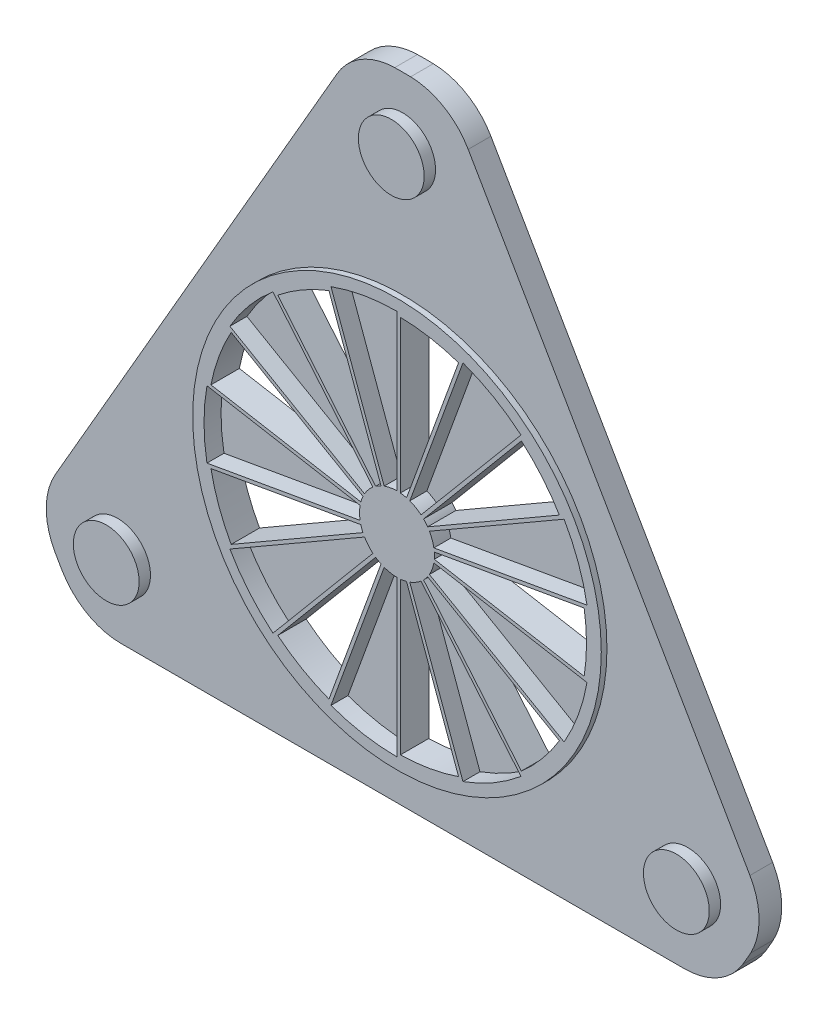
SolidWorks part; units mm, degrees
ref_plane "Спереди" through (0, 0, 0) normal (0, 0, 1) x (1, 0, 0)
ref_plane "Сверху" through (0, 0, 0) normal (0, 1, 0) x (1, 0, 0)
ref_plane "Справа" through (0, 0, 0) normal (1, 0, 0) x (0, 0, -1)
sketch "Sketch1" plane through (0, 0, 0) normal (0, 0, 1) x (1, 0, 0)
  line L0 (3.9, 6.755) -> (7.8, 0) construction
  line L2 (5.85, 10.1325) -> (11.7, 0) construction
  line L4 (7.8, 13.51) -> (15.6, 0) construction
  circle A61 centre (0, 0) radius 20
  circle A131 centre (0, 0) radius 1.25
  circle A484 centre (3.9, 0) radius 1.25
  circle A485 centre (7.8, 0) radius 1.25
  circle A486 centre (11.7, 0) radius 1.25
  circle A487 centre (15.6, 0) radius 1.25
  circle A488 centre (1.95, -3.3775) radius 1.25
  circle A489 centre (3.9, -6.755) radius 1.25
  circle A490 centre (5.85, -10.1325) radius 1.25
  circle A491 centre (7.8, -13.51) radius 1.25
  circle A492 centre (-1.95, -3.3775) radius 1.25
  circle A493 centre (-3.9, -6.755) radius 1.25
  circle A494 centre (-5.85, -10.1325) radius 1.25
  circle A495 centre (-7.8, -13.51) radius 1.25
  circle A496 centre (-3.9, 0) radius 1.25
  circle A497 centre (-7.8, 0) radius 1.25
  circle A498 centre (-11.7, 0) radius 1.25
  circle A499 centre (-15.6, 0) radius 1.25
  circle A500 centre (-1.95, 3.3775) radius 1.25
  circle A501 centre (-3.9, 6.755) radius 1.25
  circle A502 centre (-5.85, 10.1325) radius 1.25
  circle A503 centre (-7.8, 13.51) radius 1.25
  circle A504 centre (1.95, 3.3775) radius 1.25
  circle A505 centre (3.9, 6.755) radius 1.25
  circle A506 centre (5.85, 10.1325) radius 1.25
  circle A507 centre (7.8, 13.51) radius 1.25
  circle A508 centre (5.85, 3.3775) radius 1.25
  circle A509 centre (7.8, 6.755) radius 1.25
  circle A510 centre (9.75, 3.3775) radius 1.25
  circle A511 centre (11.7, 6.755) radius 1.25
  circle A512 centre (9.7491, 10.1341) radius 1.25
  circle A513 centre (13.6509, 3.3759) radius 1.25
  circle A514 centre (5.85, -3.3791) radius 1.25
  circle A515 centre (9.75, -3.3791) radius 1.25
  circle A516 centre (7.8, -6.7566) radius 1.25
  circle A517 centre (11.7, -6.7566) radius 1.25
  circle A518 centre (9.7491, -10.1356) radius 1.25
  circle A519 centre (13.6509, -3.3775) radius 1.25
  circle A520 centre (-0.0013, -6.7573) radius 1.25
  circle A521 centre (1.9487, -10.1348) radius 1.25
  circle A522 centre (-1.9513, -10.1348) radius 1.25
  circle A523 centre (-0.0013, -13.5123) radius 1.25
  circle A524 centre (-3.9032, -13.5123) radius 1.25
  circle A525 centre (3.9005, -13.5123) radius 1.25
  circle A526 centre (-5.8527, -3.3791) radius 1.25
  circle A527 centre (-7.8027, -6.7566) radius 1.25
  circle A528 centre (-9.7527, -3.3791) radius 1.25
  circle A529 centre (-11.7027, -6.7566) radius 1.25
  circle A530 centre (-13.6536, -3.3775) radius 1.25
  circle A531 centre (-9.7518, -10.1356) radius 1.25
  circle A532 centre (-5.8527, 3.3775) radius 1.25
  circle A533 centre (-9.7527, 3.3775) radius 1.25
  circle A534 centre (-7.8027, 6.755) radius 1.25
  circle A535 centre (-11.7027, 6.755) radius 1.25
  circle A536 centre (-9.7518, 10.1341) radius 1.25
  circle A537 centre (-13.6536, 3.3759) radius 1.25
  circle A538 centre (-0.0014, 6.7558) radius 1.25
  circle A539 centre (-1.9514, 10.1333) radius 1.25
  circle A540 centre (1.9486, 10.1333) radius 1.25
  circle A541 centre (-0.0014, 13.5108) radius 1.25
  circle A542 centre (3.9005, 13.5108) radius 1.25
  circle A543 centre (-3.9032, 13.5108) radius 1.25
  circle A544 centre (13.65, -1.1258) radius 2.2517 construction
  circle A545 centre (11.7009, -4.5044) radius 2.2522 construction
  circle A546 centre (9.75, -7.8834) radius 2.2522 construction
  circle A547 centre (7.7987, -11.2591) radius 2.2509 construction
  circle A548 centre (13.65, -1.1258) radius 0.65
  circle A549 centre (11.7009, -4.5044) radius 0.65
  circle A550 centre (9.75, -7.8834) radius 0.65
  circle A551 centre (7.7987, -11.2591) radius 0.65
  circle A552 centre (9.75, -1.1258) radius 0.65
  circle A553 centre (7.8009, -4.5044) radius 0.65
  circle A554 centre (5.85, -7.8834) radius 0.65
  circle A555 centre (3.8987, -11.2591) radius 0.65
  circle A556 centre (5.85, -1.1258) radius 0.65
  circle A557 centre (3.9009, -4.5044) radius 0.65
  circle A558 centre (1.95, -7.8834) radius 0.65
  circle A559 centre (-0.0013, -11.2591) radius 0.65
  circle A560 centre (1.95, -1.1258) radius 0.65
  circle A561 centre (0.0009, -4.5044) radius 0.65
  circle A562 centre (-1.95, -7.8834) radius 0.65
  circle A563 centre (-3.9013, -11.2591) radius 0.65
  circle A564 centre (-1.95, -1.1258) radius 0.65
  circle A565 centre (-3.8991, -4.5044) radius 0.65
  circle A566 centre (-5.85, -7.8834) radius 0.65
  circle A567 centre (-7.8013, -11.2591) radius 0.65
  circle A568 centre (-5.85, -1.1258) radius 0.65
  circle A569 centre (-7.7991, -4.5044) radius 0.65
  circle A570 centre (-9.75, -7.8834) radius 0.65
  circle A572 centre (-9.75, -1.1258) radius 0.65
  circle A573 centre (-11.6991, -4.5044) radius 0.65
  circle A576 centre (-13.65, -1.1258) radius 0.65
  circle A587 centre (0, 2.2517) radius 2.2517 construction
  circle A588 centre (0, 2.2517) radius 0.65
  circle A589 centre (3.9, 2.2517) radius 0.65
  circle A590 centre (7.8, 2.2517) radius 0.65
  circle A591 centre (11.7, 2.2517) radius 0.65
  circle A592 centre (15.6, 2.2517) radius 0.65
  circle A593 centre (1.9491, 5.6297) radius 2.2522 construction
  circle A594 centre (1.9491, 5.6297) radius 0.65
  circle A595 centre (5.8491, 5.6297) radius 0.65
  circle A596 centre (9.7491, 5.6297) radius 0.65
  circle A597 centre (13.6491, 5.6297) radius 0.65
  circle A598 centre (3.8991, 9.0072) radius 2.2522 construction
  circle A599 centre (3.8991, 9.0072) radius 0.65
  circle A600 centre (7.7991, 9.0072) radius 0.65
  circle A601 centre (11.6991, 9.0072) radius 0.65
  circle A602 centre (5.85, 12.3842) radius 2.2517 construction
  circle A603 centre (5.85, 12.3842) radius 0.65
  circle A604 centre (9.75, 12.3842) radius 0.65
  circle A605 centre (5.85, -14.6358) radius 0.65
  circle A606 centre (1.9509, -14.6353) radius 0.65
  circle A607 centre (-1.9491, -14.6353) radius 0.65
  circle A608 centre (-5.85, -14.6358) radius 0.65
  circle A609 centre (-15.6, 2.2517) radius 0.65
  circle A610 centre (-13.65, 5.6281) radius 0.65
  circle A611 centre (-11.7, 9.0056) radius 0.65
  circle A612 centre (-9.75, 12.3842) radius 0.65
  circle A613 centre (-5.85, 12.3842) radius 0.65
  circle A614 centre (-1.95, 12.3842) radius 0.65
  circle A615 centre (1.95, 12.3842) radius 0.65
  circle A616 centre (-7.8, 9.0056) radius 0.65
  circle A617 centre (-9.75, 5.6281) radius 0.65
  circle A618 centre (-11.7, 2.2517) radius 0.65
  circle A619 centre (-3.9, 9.0056) radius 0.65
  circle A620 centre (-5.85, 5.6281) radius 0.65
  circle A621 centre (-7.8, 2.2517) radius 0.65
  circle A622 centre (0, 9.0056) radius 0.65
  circle A623 centre (-1.95, 5.6281) radius 0.65
  circle A624 centre (-3.9, 2.2517) radius 0.65
  circle A625 centre (-15.5991, -4.5044) radius 0.65
  circle A626 centre (-13.65, -7.8834) radius 0.65
  circle A627 centre (-17.55, -7.8834) radius 0.65
  circle A628 centre (-19.5013, -11.2591) radius 0.65
  circle A629 centre (-15.6013, -11.2591) radius 0.65
  circle A630 centre (-11.7013, -11.2591) radius 0.65
  point P51 (0, 0)
  point P125 (-0.0013, -0.0008)
  point P231 (0, 0)
  dimension "D1" = 5
  dimension "D3" = 6
  dimension "D5" = 8
  dimension "D7" = 4
  dimension "D11" = 4
  dimension "D2" = 6
  dimension "D6" = 5
  dimension "D8" = 3
  dimension "D9" = 2
  dimension "D4" = 1.3
  dimension "D10" = 3
ref_plane "Plane1" through (0, 0, 10) normal (0, 0, 1) x (1, 0, 0)
sketch "Sketch2" plane through (0, 0, 10) normal (0, 0, 1) x (1, 0, 0)
  line L0 (0, 2.9883) -> (0, 17)
  line L62 (1.0221, 2.8081) -> (5.8143, 15.9748)
  line L71 (1.9208, 2.2892) -> (10.9274, 13.0228)
  line L92 (2.588, 1.4942) -> (14.7224, 8.5)
  line L101 (2.9429, 0.5189) -> (16.7417, 2.952)
  line L110 (2.9429, -0.5189) -> (16.7417, -2.952)
  line L119 (2.588, -1.4942) -> (14.7224, -8.5)
  line L124 (1.9208, -2.2892) -> (10.9274, -13.0228)
  line L133 (1.0221, -2.8081) -> (5.8143, -15.9748)
  line L142 (0, -2.9883) -> (0, -17)
  line L151 (-1.0221, -2.8081) -> (-5.8143, -15.9748)
  line L160 (-1.9208, -2.2892) -> (-10.9274, -13.0228)
  line L165 (-2.588, -1.4942) -> (-14.7224, -8.5)
  line L168 (-2.9429, -0.5189) -> (-16.7417, -2.952)
  line L171 (-2.9429, 0.5189) -> (-16.7417, 2.952)
  line L174 (-2.588, 1.4942) -> (-14.7224, 8.5)
  line L177 (-1.9208, 2.2892) -> (-10.9274, 13.0228)
  line L180 (-1.0221, 2.8081) -> (-5.8143, 15.9748)
  line L183 (0.3, 3.2863) -> (0.3, 16.6948)
  line L185 (5.4281, 15.7906) -> (0.8421, 3.1908)
  line L186 (14.3082, 8.6072) -> (2.696, 1.903)
  line L187 (2.3422, 2.3246) -> (10.9611, 12.5962)
  line L188 (16.4933, -2.6036) -> (3.2885, -0.2752)
  line L189 (3.2885, 0.2752) -> (16.4933, 2.6036)
  line L190 (10.9611, -12.5962) -> (2.3422, -2.3246)
  line L191 (2.696, -1.903) -> (14.3082, -8.6072)
  line L192 (0.3, -16.6948) -> (0.3, -3.2863)
  line L193 (0.8421, -3.1908) -> (5.4281, -15.7906)
  line L194 (-10.5014, -12.9818) -> (-1.8826, -2.7103)
  line L195 (-1.4059, -2.9855) -> (-5.9919, -15.5854)
  line L196 (-16.3891, -3.1945) -> (-3.1843, -0.8661)
  line L197 (-2.996, -1.3834) -> (-14.6082, -8.0876)
  line L198 (-14.6082, 8.0876) -> (-2.996, 1.3834)
  line L199 (-3.1843, 0.8661) -> (-16.3891, 3.1945)
  line L200 (-5.9919, 15.5854) -> (-1.4059, 2.9855)
  line L201 (-1.8826, 2.7103) -> (-10.5014, 12.9818)
  circle A52 centre (0, 0) radius 17
  circle A53 centre (0, 0) radius 18
  circle A199 centre (0, 0) radius 2.9883
  circle A245 centre (0, 0) radius 18.85
  circle A246 centre (0, 0) radius 3.3
  circle A247 centre (0, 0) radius 16.6975
  point P39 (0, 0)
  point P80 (0, 0)
  point P108 (0, 0)
  dimension "D1" = 18
  dimension "D4" = 9
  dimension "D2" = 0.3
  dimension "D5" = 1
  dimension "D3" = 0.3
extrude "Boss-Extrude1" add sketch "Sketch2" against normal blind 2.5
sketch "Sketch11" plane through (0, 0, 7.5) normal (0, 0, -1) x (-1, 0, 0)
  line L0 (0, 2.9883) -> (0, 18)
  line L1 (1.0221, 2.8081) -> (6.1564, 16.9145)
  line L2 (2.588, 1.4942) -> (15.5885, 9)
  line L3 (1.9208, 2.2892) -> (11.5702, 13.7888)
  line L4 (2.9429, -0.5189) -> (17.7265, -3.1257)
  line L5 (2.9429, 0.5189) -> (17.7265, 3.1257)
  line L6 (1.9208, -2.2892) -> (11.5702, -13.7888)
  line L7 (2.588, -1.4942) -> (15.5885, -9)
  line L8 (0, -2.9883) -> (0, -18)
  line L9 (1.0221, -2.8081) -> (6.1564, -16.9145)
  line L10 (-1.9208, -2.2892) -> (-11.5702, -13.7888)
  line L11 (-1.0221, -2.8081) -> (-6.1564, -16.9145)
  line L12 (-2.9429, -0.5189) -> (-17.7265, -3.1257)
  line L13 (-2.588, -1.4942) -> (-15.5885, -9)
  line L14 (-2.588, 1.4942) -> (-15.5885, 9)
  line L15 (-2.9429, 0.5189) -> (-17.7265, 3.1257)
  line L16 (-1.0221, 2.8081) -> (-6.1564, 16.9145)
  line L17 (-1.9208, 2.2892) -> (-11.5702, 13.7888)
  circle A0 centre (0, 0) radius 2.9883
  circle A5 centre (0, 0) radius 18 construction
  arc A6 (0, 18) -> (6.1564, 16.9145) centre (0, 0) cw
  arc A8 (11.5702, 13.7888) -> (15.5885, 9) centre (0, 0) cw
  arc A10 (17.7265, 3.1257) -> (17.7265, -3.1257) centre (0, 0) cw
  arc A12 (15.5885, -9) -> (11.5702, -13.7888) centre (0, 0) cw
  arc A14 (6.1564, -16.9145) -> (0, -18) centre (0, 0) cw
  arc A16 (-6.1564, -16.9145) -> (-11.5702, -13.7888) centre (0, 0) cw
  arc A18 (-15.5885, -9) -> (-17.7265, -3.1257) centre (0, 0) cw
  arc A20 (-17.7265, 3.1257) -> (-15.5885, 9) centre (0, 0) cw
  arc A22 (-11.5702, 13.7888) -> (-6.1564, 16.9145) centre (0, 0) cw
  point P63 (0, 0)
  dimension "D1" = 9
extrude "Boss-Extrude7" add sketch "Sketch11" against normal blind 1 contours A8 L3 A0 L2 | A10 L5 A0 L4 | A12 L7 A0 L6 | A14 L9 A0 L8 | A16 L11 A0 L10 | A18 L13 A0 L12 | A20 L15 A0 L14 | A22 L17 A0 L16 | A6 L0 A0 L1
sketch "Sketch13" plane through (0, 0, 7.5) normal (0, 0, -1) x (-1, 0, 0)
  circle A0 centre (0, 0) radius 3.3
extrude "Boss-Extrude8" [suppressed] add sketch "Sketch13" against normal blind 3
sketch "Sketch14" plane through (0, 0, 10) normal (0, 0, 1) x (1, 0, 0)
  circle A0 centre (0, 0) radius 17
  arc A1 (0, 17) -> (-5.8143, 15.9748) centre (0, 0) ccw construction
sketch "Sketch9" plane through (0, 0, 10) normal (0, 0, 1) x (1, 0, 0)
  circle A0 centre (0, 0) radius 3.0981
sketch "Sketch16" plane through (0, 0, 8.5) normal (0, 0, 1) x (1, 0, 0)
  circle A0 centre (0, 0) radius 3.3
sketch "Sketch17" plane through (0, 0, 7.5) normal (0, 0, -1) x (-1, 0, 0)
  circle A0 centre (0, 0) radius 3.3
extrude "Boss-Extrude9" add sketch "Sketch17" against normal blind 2.5
extrude "Boss-Extrude5" add sketch "Sketch9" against normal up to surface (2.5 mm away)
sketch "Sketch3" plane through (0, 0, 7.5) normal (0, 0, -1) x (-1, 0, 0)
  circle A0 centre (0, 0) radius 17.6
  circle A1 centre (0, 0) radius 35
  circle M33 centre (0, 0) radius 18
extrude "Boss-Extrude2" add sketch "Sketch3" against normal blind 2 contours A1 M33
sketch "Sketch4" plane through (0, 0, 7.5) normal (0, 0, -1) x (-1, 0, 0)
  circle A0 centre (0, 0) radius 29 construction
  circle A1 centre (0, 29) radius 2.9
  circle A2 centre (25.1147, -14.5) radius 2.9
  circle A3 centre (-25.1147, -14.5) radius 2.9
  point P11 (0, 0)
  dimension "D1" = 3
extrude "Boss-Extrude3" add sketch "Sketch4" against normal blind 3
sketch "Sketch6" plane through (0, 0, 9.5) normal (0, 0, -1) x (-1, 0, 0)
  circle A0 centre (0, 30) radius 5
  circle A2 centre (25.9808, -15) radius 5
  circle A3 centre (-25.9808, -15) radius 5
  point P10 (0, 0)
  dimension "D1" = 3
extrude "Boss-Extrude4" add sketch "Sketch6" along normal blind 1
sketch "Sketch7" plane through (0, 0, 7.5) normal (0, 0, -1) x (-1, 0, 0)
  line L1 (0, 42) -> (-36.3731, -21)
  line L2 (-36.3731, -21) -> (36.3731, -21)
  line L3 (36.3731, -21) -> (0, 42)
  circle A2 centre (0, 0) radius 21 construction
  circle A3 centre (0, 0) radius 59.1314
extrude "Cut-Extrude1" cut sketch "Sketch7" against normal blind 10
fillet "Fillet1" radius 6 6 edges at (-32.1865, -13.7487, 8.5) (-4.1865, 34.7487, 8.5) (28, -21, 8.5) (-28, -21, 8.5) (4.1865, 34.7487, 8.5) (32.1865, -13.7487, 8.5)
